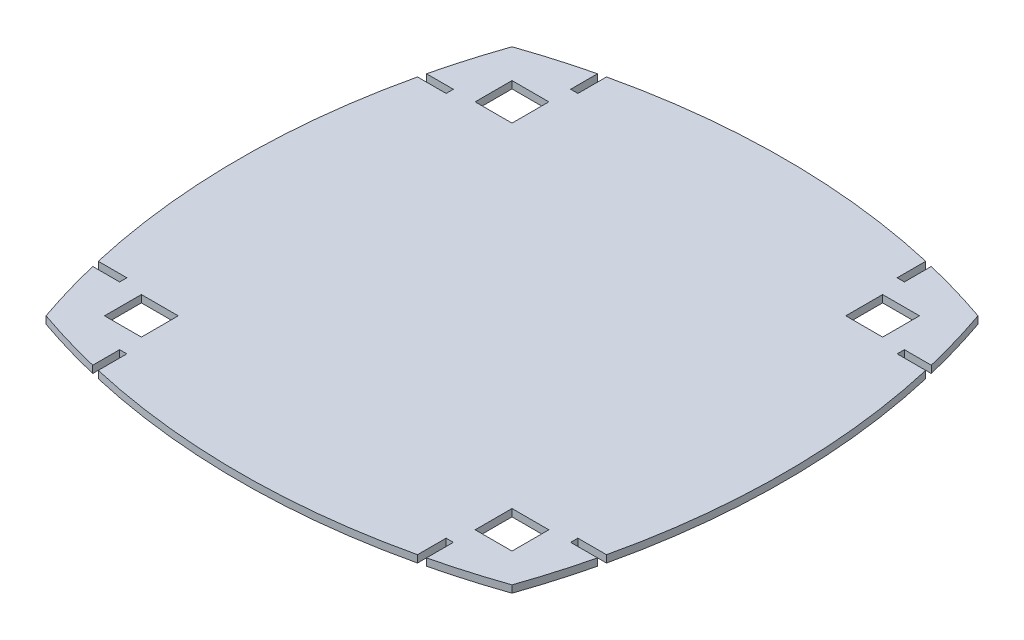
SolidWorks part; units mm, degrees
ref_plane "Front Plane" through (0, 0, 0) normal (0, 0, 1) x (1, 0, 0)
ref_plane "Top Plane" through (0, 0, 0) normal (0, 1, 0) x (1, 0, 0)
ref_plane "Right Plane" through (0, 0, 0) normal (1, 0, 0) x (0, 0, -1)
sketch "Sketch1" plane through (0, 0, 0) normal (0, 1, 0) x (1, 0, 0)
  line L0 (110, 155.4) -> (110, 175.1126)
  line L1 (-160.565, 160.565) -> (160.565, 160.565) construction
  line L2 (-160.565, 160.565) -> (-160.565, -160.565) construction
  line L3 (-160.565, -160.565) -> (160.565, -160.565) construction
  line L4 (160.565, 160.565) -> (160.565, -160.565) construction
  line L5 (0, -160.565) -> (0, -100) construction
  line L6 (-160.565, 0) -> (-100, 0) construction
  line L7 (-140.4, 140.4) -> (140.4, 140.4) construction
  line L8 (-140.4, 140.4) -> (-140.4, -140.4) construction
  line L9 (-140.4, -140.4) -> (140.4, -140.4) construction
  line L10 (140.4, 140.4) -> (140.4, -140.4) construction
  line L11 (0, -140.4) -> (0, 140.4) construction
  line L12 (-140.4, 0) -> (0, 0) construction
  line L13 (-140.4, 140.4) -> (-115, 140.4)
  line L14 (-140.4, 140.4) -> (-140.4, 115)
  line L15 (-140.4, 115) -> (-115, 115)
  line L16 (-115, 140.4) -> (-115, 115)
  line L17 (-115, 155.4) -> (-110, 155.4)
  line L18 (-115, 155.4) -> (-115, 173.9331)
  line L19 (115, 155.4) -> (115, 173.9331)
  line L20 (-110, 155.4) -> (-110, 175.1126)
  line L21 (-155.4, 115) -> (-173.9331, 115)
  line L22 (-155.4, 115) -> (-155.4, 110)
  line L23 (-155.4, 110) -> (-175.1126, 110)
  line L24 (115, 155.4) -> (110, 155.4)
  line L25 (140.4, 140.4) -> (115, 140.4)
  line L26 (115, 140.4) -> (115, 115)
  line L27 (140.4, 140.4) -> (140.4, 115)
  line L28 (140.4, 115) -> (115, 115)
  line L29 (155.4, 115) -> (155.4, 110)
  line L30 (155.4, 115) -> (173.9331, 115)
  line L31 (155.4, 110) -> (175.1126, 110)
  line L32 (115, -155.4) -> (115, -173.9331)
  line L33 (110, -155.4) -> (110, -175.1126)
  line L34 (115, -155.4) -> (110, -155.4)
  line L35 (155.4, -115) -> (173.9331, -115)
  line L36 (155.4, -115) -> (155.4, -110)
  line L37 (155.4, -110) -> (175.1126, -110)
  line L38 (140.4, -140.4) -> (140.4, -115)
  line L39 (140.4, -140.4) -> (115, -140.4)
  line L40 (115, -140.4) -> (115, -115)
  line L41 (140.4, -115) -> (115, -115)
  line L42 (-140.4, -140.4) -> (-115, -140.4)
  line L43 (-110, -155.4) -> (-110, -175.1126)
  line L44 (-115, -155.4) -> (-115, -173.9331)
  line L45 (-115, -155.4) -> (-110, -155.4)
  line L46 (-115, -140.4) -> (-115, -115)
  line L47 (-140.4, -140.4) -> (-140.4, -115)
  line L48 (-140.4, -115) -> (-115, -115)
  line L49 (-155.4, -115) -> (-155.4, -110)
  line L50 (-155.4, -115) -> (-173.9331, -115)
  line L51 (-155.4, -110) -> (-175.1126, -110)
  line L52 (0, 100) -> (0, 160.565) construction
  line L53 (0, 0) -> (160.565, 0) construction
  line L54 (100, 0) -> (140.4, 0) construction
  line L57 (0, -100) -> (0, 100) construction
  line L58 (-100, 0) -> (100, 0) construction
  arc A0 (-160.565, 160.565) -> (-115, 173.9331) centre (0, -302.3809) cw
  arc A1 (160.565, 160.565) -> (173.9331, 115) centre (-302.3809, 0) cw
  arc A2 (160.565, -160.565) -> (115, -173.9331) centre (0, 302.3809) cw
  arc A3 (-160.565, -160.565) -> (-173.9331, -115) centre (302.3809, 0) cw
  arc A4 (-110, 175.1126) -> (110, 175.1126) centre (0, -302.3809) cw
  arc A5 (-173.9331, 115) -> (-160.565, 160.565) centre (302.3809, 0) cw
  arc A6 (115, 173.9331) -> (160.565, 160.565) centre (0, -302.3809) cw
  arc A7 (175.1126, 110) -> (175.1126, -110) centre (-302.3809, 0) cw
  arc A8 (173.9331, -115) -> (160.565, -160.565) centre (-302.3809, 0) cw
  arc A9 (110, -175.1126) -> (-110, -175.1126) centre (0, 302.3809) cw
  arc A10 (-115, -173.9331) -> (-160.565, -160.565) centre (0, 302.3809) cw
  arc A11 (-175.1126, -110) -> (-175.1126, 110) centre (302.3809, 0) cw
  point P0 (0, 0)
  point P8 (0, 0)
  point P56 (0, 0)
  point P57 (0, 0)
  point P58 (0, 0)
  point P60 (0, 0)
  dimension "D2" = 490
  dimension "D1" = 321.13
  dimension "D3" = 280.8
  dimension "D4" = 25.4
  dimension "D5" = 5
  dimension "D6" = 5
  dimension "D7" = 15
  dimension "D8" = 15
extrude "Boss-Extrude1" add sketch "Sketch1" along normal blind 5
